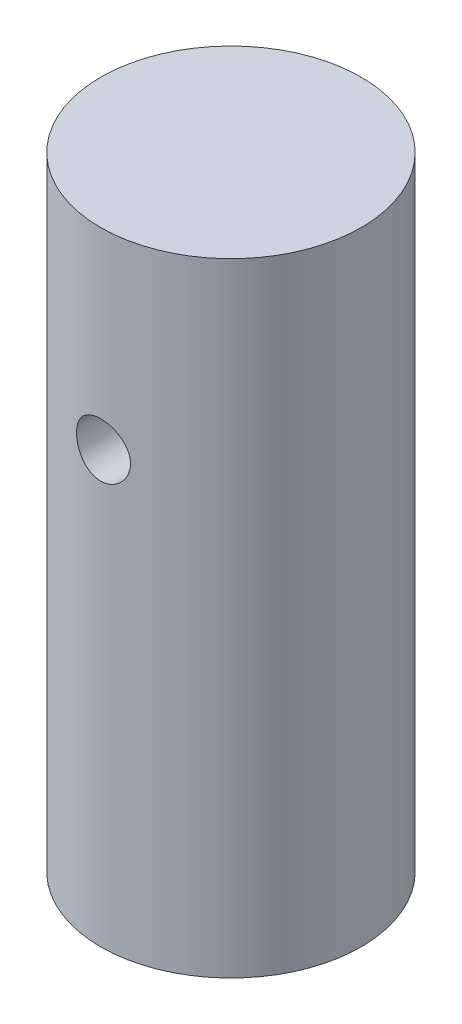
SolidWorks part; units mm, degrees
material "Gray Cast Iron"
ref_plane "Front Plane" through (0, 0, 0) normal (0, 0, 1) x (1, 0, 0)
ref_plane "Top Plane" through (0, 0, 0) normal (0, 1, 0) x (1, 0, 0)
ref_plane "Right Plane" through (0, 0, 0) normal (1, 0, 0) x (0, 0, -1)
sketch "Sketch1" plane through (0, 0, 0) normal (0, 1, 0) x (1, 0, 0)
  circle A0 centre (0, 0) radius 23
  dimension "D1" = 46
extrude "Boss-Extrude1" add sketch "Sketch1" along normal blind 110
sketch "Sketch2" plane through (0, 0, 0) normal (0, 0, 1) x (1, 0, 0)
  circle A0 centre (0, 76) radius 4.7625
  dimension "D1" = 9.525
extrude "Cut-Extrude1" cut sketch "Sketch2" against normal mid plane 50
